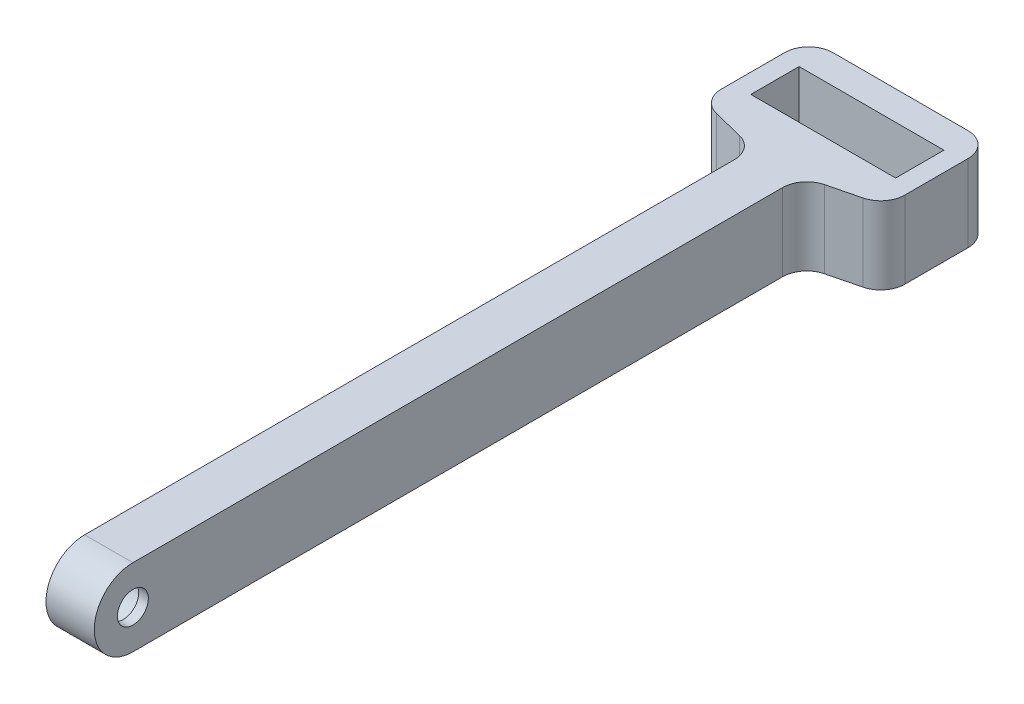
SolidWorks part; units mm, degrees
ref_plane "Plan de face" through (0, 0, 0) normal (0, 0, 1) x (1, 0, 0)
ref_plane "Plan de dessus" through (0, 0, 0) normal (0, 1, 0) x (1, 0, 0)
ref_plane "Plan de droite" through (0, 0, 0) normal (1, 0, 0) x (0, 0, -1)
sketch "Esquisse1" plane through (0, 0, 0) normal (1, 0, 0) x (0, 0, -1)
  line L0 (0, 10.3529) -> (0, -13.1447) construction
  line L1 (-24.1024, 0) -> (26.9408, 0) construction
  line L2 (-30, 4) -> (41, 4)
  line L3 (41, 4) -> (41, -4)
  line L4 (41, -4) -> (-30, -4)
  line L5 (-34, 8.3056) -> (-34, -12.2141) construction
  circle A0 centre (-30, 0) radius 1.6
  circle A1 centre (-30, 0) radius 4 construction
  arc A2 (-30, 4) -> (-30, -4) centre (-30, 0) ccw
  dimension "D1" = 3.2
  dimension "D2" = 75
  dimension "D3" = 8
  dimension "D4" = 30
extrude "Boss.-Extru.1" add sketch "Esquisse1" along normal blind 5 contours L4 A2 L2 L3
sketch "Esquisse3" plane through (0, 4, 0) normal (0, 1, 0) x (1, 0, 0)
  line L0 (2.5, 41) -> (2.5, 52) construction
  line L1 (0, 41) -> (-7, 41)
  line L2 (-7, 41) -> (-7, 52)
  line L3 (-7, 52) -> (12, 52)
  line L4 (0, 41) -> (0, -30)
  line L5 (0, -30) -> (5, -30)
  line L6 (0, 41) -> (0, -30)
  line L7 (5, 41) -> (0, 41)
  line L9 (0, -30) -> (5, -30)
  line L11 (5, 41) -> (0, 41)
  line L12 (5, 41) -> (12, 41)
  line L13 (12, 41) -> (12, 52)
  line L14 (-7, 41) -> (5, 38)
  line L15 (10, 44) -> (-5, 44)
  line L16 (10, 44) -> (10, 49)
  line L17 (10, 49) -> (-5, 49)
  line L18 (-5, 44) -> (-5, 49)
  line L19 (10, 44) -> (-5, 49) construction
  line L20 (10, 49) -> (-5, 44) construction
  line L21 (12, 41) -> (0, 38)
  line L26 (5, -30) -> (5, 41)
  line L27 (5, -30) -> (5, 41)
  point P9 (2.5, 46.5)
  point P11 (2.5, 52)
  dimension "D2" = 15
  dimension "D3" = 2
  dimension "D4" = 3
  dimension "D5" = 3
  dimension "D6" = 5
  dimension "D1" = 0
extrude "Boss.-Extru.2" add sketch "Esquisse3" along direction (0, 1, 0) on the side against the normal blind 8
sketch "Esquisse4" plane through (0, 0, 0) normal (-1, 0, 0) x (0, 0, 1)
  line L3 (30, 4) -> (-39.25, 4)
  line L4 (-39.25, 4) -> (-39.25, -4)
  line L5 (-39.25, -4) -> (30, -4)
  line L6 (30, 4) -> (-39.25, 4)
  line L8 (-39.25, -4) -> (30, -4)
  line L9 (-39.25, 4) -> (-39.25, -4)
  circle A0 centre (30, 0) radius 2.4
  arc A1 (30, -4) -> (30, 4) centre (30, 0) ccw
  arc A2 (30, -4) -> (30, 4) centre (30, 0) ccw
  dimension "D2" = 4.8
  dimension "D1" = 0
extrude "Enlèv. mat.-Extru.1" cut sketch "Esquisse4" against normal blind 4 contours A0
fillet "Congé2" radius 2.5 6 edges at (5, 0, -39.25) (12, 0, -41) (12, 0, -52) (-7, 0, -52) (-7, 0, -41) (0, 0, -39.25)
